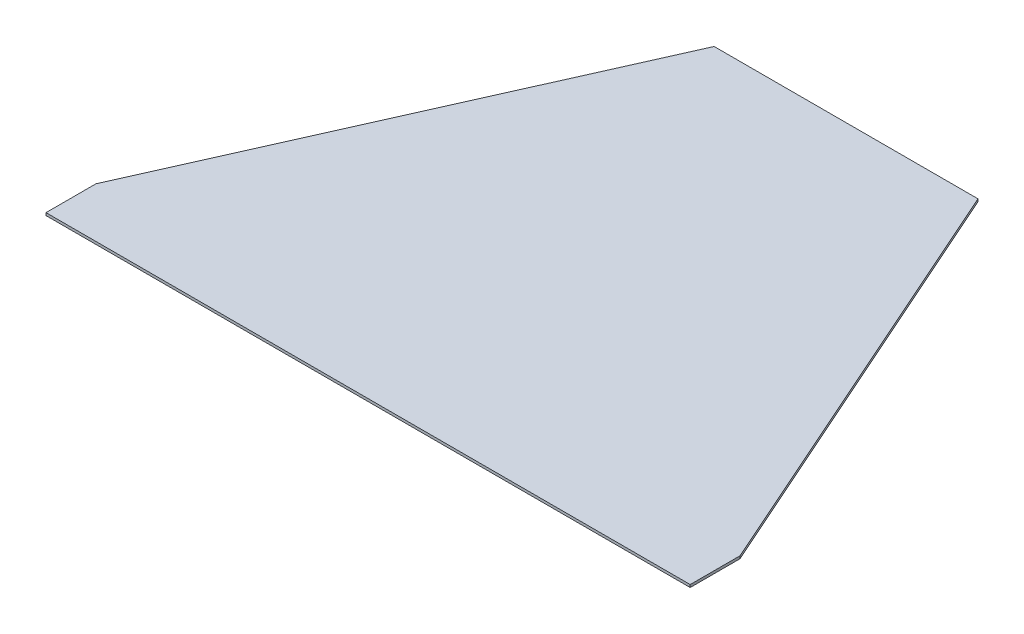
SolidWorks part; units mm, degrees
ref_plane "前视基准面" through (0, 0, 0) normal (0, 0, 1) x (1, 0, 0)
ref_plane "上视基准面" through (0, 0, 0) normal (0, 1, 0) x (1, 0, 0)
ref_plane "右视基准面" through (0, 0, 0) normal (1, 0, 0) x (0, 0, -1)
sketch "草图1" plane through (0, 0, 0) normal (0, 1, 0) x (1, 0, 0)
  line L0 (0, 0) -> (0, 920) construction
  line L1 (-620, 0) -> (620, 0)
  line L2 (-254, 920) -> (254, 920)
  line L3 (-620, 0) -> (-620, 96)
  line L4 (-620, 96) -> (-254, 920)
  line L5 (620, 96) -> (254, 920)
  line L6 (620, 0) -> (620, 96)
  dimension "D1" = 920
  dimension "D2" = 1240
  dimension "D3" = 96
  dimension "D4" = 508
extrude "凸台-拉伸1" add sketch "草图1" along normal blind 5
